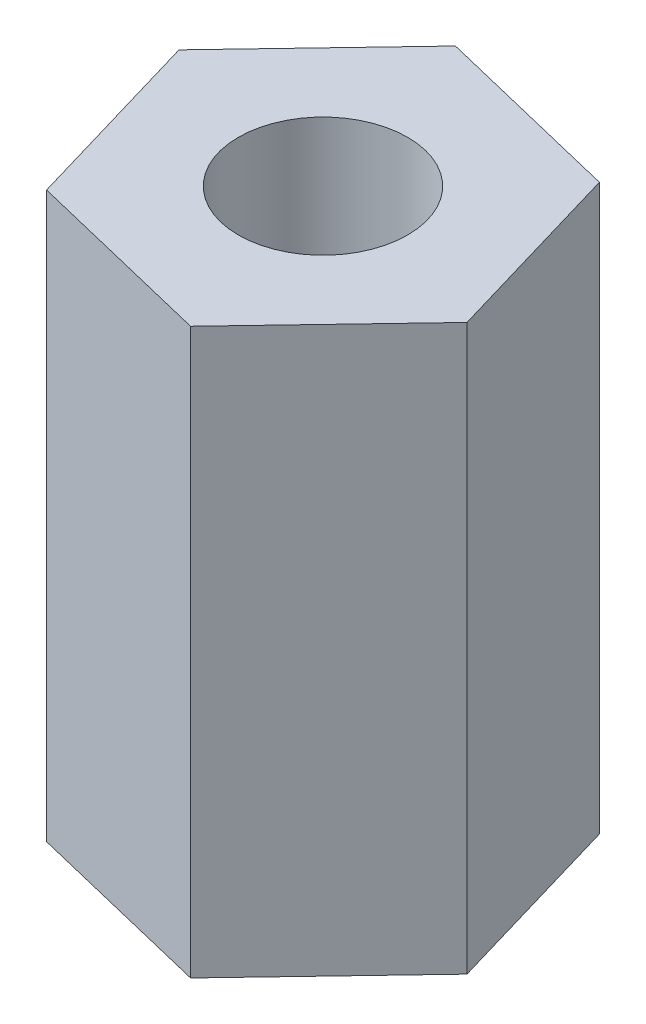
SolidWorks part; units mm, degrees
material "Thornel VCB-20 Carbon Cloth"
ref_plane "Front Plane" through (0, 0, 0) normal (0, 0, 1) x (1, 0, 0)
ref_plane "Top Plane" through (0, 0, 0) normal (0, 1, 0) x (1, 0, 0)
ref_plane "Right Plane" through (0, 0, 0) normal (1, 0, 0) x (0, 0, -1)
sketch "Sketch1" plane through (0, 0, 0) normal (0, 1, 0) x (1, 0, 0)
  line L1 (0.9773, -3.3234) -> (3.3668, -0.8153)
  line L2 (3.3668, -0.8153) -> (2.3895, 2.508)
  line L3 (2.3895, 2.508) -> (-0.9773, 3.3234)
  line L4 (-0.9773, 3.3234) -> (-3.3668, 0.8153)
  line L5 (-3.3668, 0.8153) -> (-2.3895, -2.508)
  line L6 (-2.3895, -2.508) -> (0.9773, -3.3234)
  circle A0 centre (0, 0) radius 1.5
  circle A1 centre (0, 0) radius 3 construction
  dimension "D1" = 3
  dimension "D2" = 6
extrude "Boss-Extrude1" add sketch "Sketch1" along normal mid plane 10
